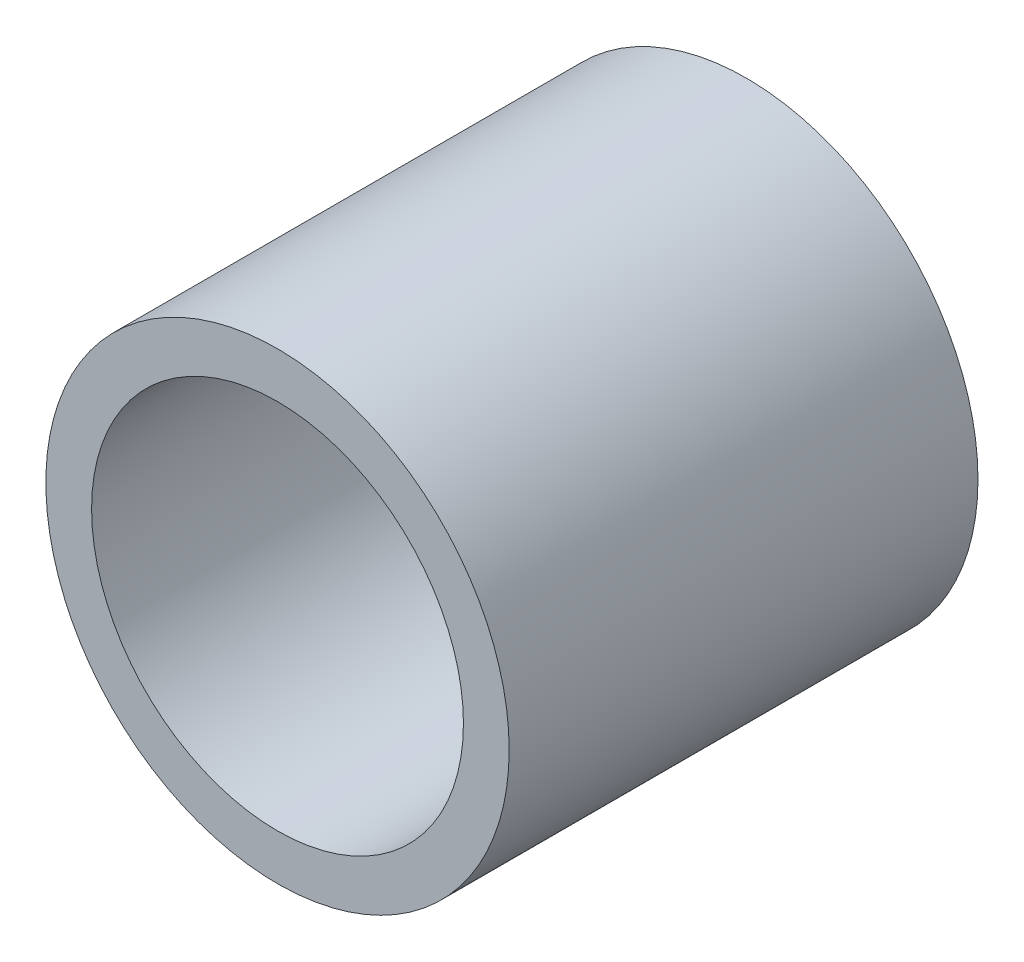
SolidWorks part; units mm, degrees
ref_plane "Front Plane" through (0, 0, 0) normal (0, 0, 1) x (1, 0, 0)
ref_plane "Top Plane" through (0, 0, 0) normal (0, 1, 0) x (1, 0, 0)
ref_plane "Right Plane" through (0, 0, 0) normal (1, 0, 0) x (0, 0, -1)
sketch "Sketch1" plane through (0, 0, 0) normal (0, 0, 1) x (1, 0, 0)
  circle A0 centre (0, 0) radius 4.065
  circle A1 centre (0, 0) radius 5.065
  dimension "D1" = 10.13
  dimension "D2" = 1
extrude "Boss-Extrude1" add sketch "Sketch1" along normal blind 10.25
